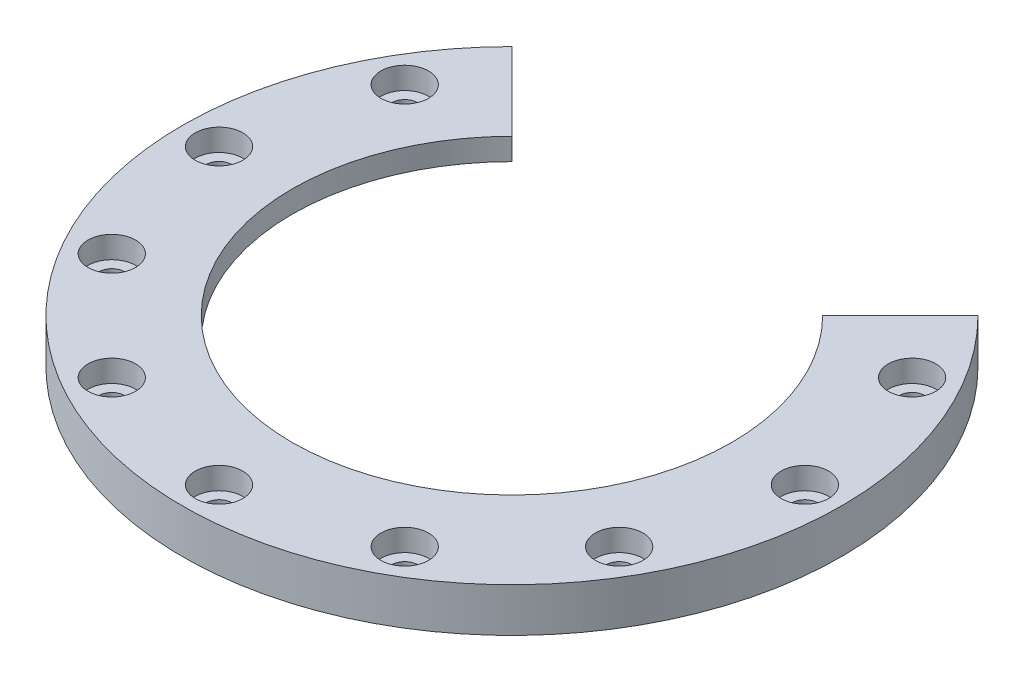
SolidWorks part; units mm, degrees
ref_plane "Front Plane" through (0, 0, 0) normal (0, 0, 1) x (1, 0, 0)
ref_plane "Top Plane" through (0, 0, 0) normal (0, 1, 0) x (1, 0, 0)
ref_plane "Right Plane" through (0, 0, 0) normal (1, 0, 0) x (0, 0, -1)
sketch "Sketch1" plane through (0, 0, 0) normal (0, 1, 0) x (1, 0, 0)
  line L0 (0, 0) -> (0, 52.0165) construction
  circle A0 centre (0, 0) radius 45
  circle A1 centre (0, 0) radius 30
  circle A2 centre (0, 0) radius 40 construction
  circle A3 centre (0, 40) radius 1.75
  circle A4 centre (0, 0) radius 35 construction
  circle A5 centre (20, 34.641) radius 1.75
  circle A6 centre (34.641, 20) radius 1.75
  circle A7 centre (40, 0) radius 1.75
  circle A8 centre (34.641, -20) radius 1.75
  circle A9 centre (20, -34.641) radius 1.75
  circle A10 centre (0, -40) radius 1.75
  circle A11 centre (-20, -34.641) radius 1.75
  circle A12 centre (-34.641, -20) radius 1.75
  circle A13 centre (-40, 0) radius 1.75
  circle A14 centre (-34.641, 20) radius 1.75
  circle A15 centre (-20, 34.641) radius 1.75
  point P21 (0, 0)
  point P34 (0, 0)
  point P48 (0, 0)
  point P72 (0, 0)
  dimension "D1" = 90
  dimension "D2" = 60
  dimension "D4" = 3.5
  dimension "D5" = 70
  dimension "D6" = 12
  dimension "D3" = 80
extrude "Boss-Extrude1" add sketch "Sketch1" along normal blind 6
sketch "Sketch2" plane through (0, 0, 0) normal (0, -1, 0) x (1, 0, 0)
  circle A0 centre (0, 0) radius 35.5
  dimension "D1" = 71
extrude "Cut-Extrude1" cut sketch "Sketch2" against normal blind 3
sketch "Sketch3" plane through (0, 6, 0) normal (0, 1, 0) x (1, 0, 0)
  line L0 (0, 0) -> (49.8808, 0) construction
  circle A0 centre (40, 0) radius 3.25
  circle A1 centre (34.641, -20) radius 3.25
  circle A2 centre (20, -34.641) radius 3.25
  circle A3 centre (0, -40) radius 3.25
  circle A4 centre (-20, -34.641) radius 3.25
  circle A5 centre (-34.641, -20) radius 3.25
  circle A6 centre (-40, 0) radius 3.25
  circle A7 centre (-34.641, 20) radius 3.25
  circle A8 centre (-20, 34.641) radius 3.25
  circle A9 centre (0, 40) radius 3.25
  circle A10 centre (20, 34.641) radius 3.25
  circle A11 centre (34.641, 20) radius 3.25
  point P30 (0, 0)
  dimension "D1" = 6.5
  dimension "D2" = 12
extrude "Cut-Extrude2" cut sketch "Sketch3" against normal blind 3
sketch "Sketch5" plane through (0, 0, 0) normal (0, 1, 0) x (1, 0, 0)
  line L0 (0, 0) -> (0, 52.0945) construction
  line L1 (38.8909, 38.8909) -> (0, 0)
  line L2 (-38.8909, 38.8909) -> (0, 0)
  arc A0 (38.8909, 38.8909) -> (-38.8909, 38.8909) centre (0, 0) ccw
  dimension "D2" = 55
  dimension "D1" = 45
extrude "Cut-Extrude4" cut sketch "Sketch5" along normal blind 10
